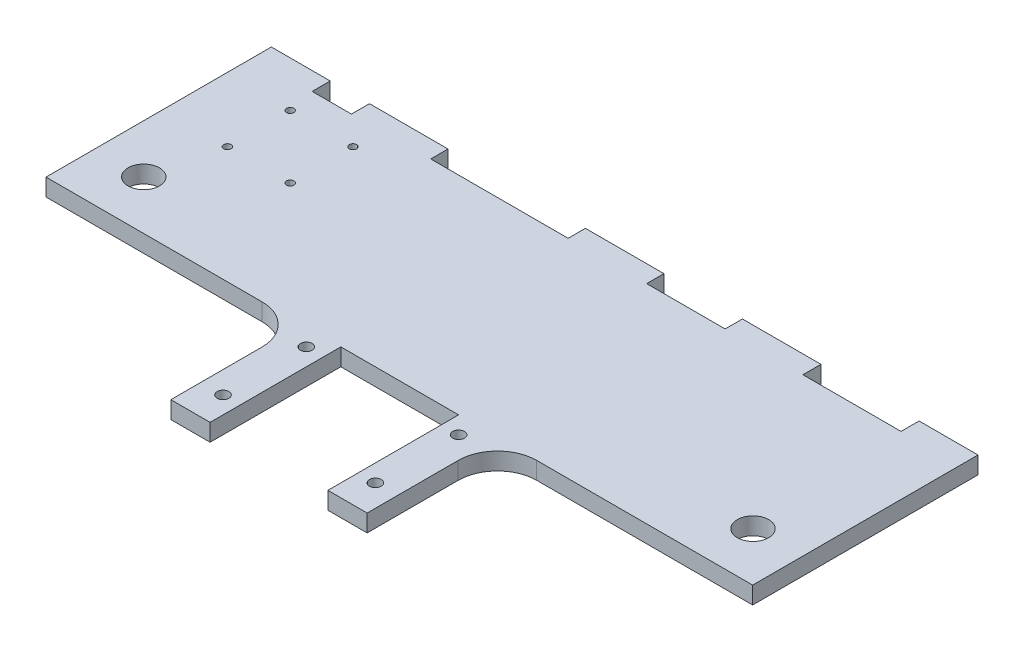
SolidWorks part; units mm, degrees
ref_plane "Front Plane" through (0, 0, 0) normal (0, 0, 1) x (1, 0, 0)
ref_plane "Top Plane" through (0, 0, 0) normal (0, 1, 0) x (1, 0, 0)
ref_plane "Right Plane" through (0, 0, 0) normal (1, 0, 0) x (0, 0, -1)
sketch "Sketch1" plane through (0, 0, 0) normal (0, 1, 0) x (1, 0, 0)
  line L0 (12.7, 67.056) -> (241.3, 67.056) construction
  line L3 (12.7, 72.898) -> (31.75, 72.898)
  line L5 (31.75, 72.898) -> (31.75, 67.056)
  line L6 (31.75, 67.056) -> (44.45, 67.056)
  line L7 (12.7, 0) -> (241.3, 0) construction
  line L8 (44.45, 67.056) -> (44.45, 72.898)
  line L10 (95.25, -42.164) -> (107.95, -42.164)
  line L12 (127, 0.1228) -> (146.05, 0.1228)
  line L13 (146.05, 0.1228) -> (146.05, -42.164)
  line L14 (127, 0.1228) -> (107.95, 0.1228)
  line L15 (107.95, 0.1228) -> (107.95, -42.164)
  line L16 (146.05, -42.164) -> (158.75, -42.164)
  line L17 (12.7, 0) -> (82.55, 0)
  line L18 (95.25, -12.7) -> (95.25, -42.164)
  line L19 (241.3, 0) -> (171.45, 0)
  line L20 (158.75, -12.7) -> (158.75, -42.164)
  line L27 (114.3, 72.898) -> (139.7, 72.898)
  line L28 (165.1, 72.898) -> (190.5, 72.898)
  line L29 (69.85, 72.898) -> (69.85, 67.31)
  line L30 (69.85, 67.31) -> (114.3, 67.31)
  line L31 (114.3, 67.31) -> (114.3, 72.898)
  line L32 (139.7, 72.898) -> (139.7, 67.31)
  line L33 (139.7, 67.31) -> (165.1, 67.31)
  line L34 (165.1, 67.31) -> (165.1, 72.898)
  line L35 (190.5, 72.898) -> (190.5, 67.056)
  line L36 (190.5, 67.056) -> (222.25, 67.056)
  line L37 (222.25, 67.056) -> (222.25, 72.898)
  line L38 (44.45, 72.898) -> (69.85, 72.898)
  line L39 (222.25, 72.898) -> (241.3, 72.898)
  line L40 (241.3, 72.898) -> (241.3, 0)
  line L41 (12.7, 72.898) -> (12.7, 0)
  arc A0 (171.45, 0) -> (158.75, -12.7) centre (171.45, -12.7) ccw
  arc A1 (95.25, -12.7) -> (82.55, 0) centre (82.55, -12.7) ccw
  point P0 (0, 0)
  point P10 (0, -41.181)
  point P27 (95.25, 0)
  dimension "D6" = 12.7
  dimension "D3" = 5.842
  dimension "D4" = 67.056
  dimension "D5" = 19.05
  dimension "D7" = 12.7
  dimension "D10" = 25.4
  dimension "D11" = 5.588
  dimension "D13" = 29.464
  dimension "D14" = 42.2868
  dimension "D15" = 12.7
  dimension "D17" = 25.4
  dimension "D20" = 228.6
extrude "Boss-Extrude1" add sketch "Sketch1" along normal blind 5.588
sketch "Sketch2" plane through (0, 0, 0) normal (0, -1, 0) x (1, 0, 0)
  point P0 (102.362, 32.3976)
  point P1 (151.638, 32.3976)
  point P3 (102.362, 5.4568)
  point P5 (151.638, 5.4568)
hole_wizard "#6 Clearance Hole1" positions "Sketch3" profile "Sketch4" hole size "#6" standard "ANSI Inch" end condition through all
sketch "Sketch3" plane through (0, 0, 0) normal (0, -1, 0) x (-1, 0, 0)
  point P0 (-102.362, -32.3976)
  point P3 (-151.638, -32.3976)
  point P6 (-151.638, -5.4568)
  point P9 (-102.362, -5.4568)
sketch "Sketch4" plane through (102.362, 0, 32.3976) normal (1, 0, 0) x (0, 0, -1)
  line L0 (0, 0) -> (0, 5.588)
  line L1 (0, 5.588) -> (1.8986, 5.588)
  line L2 (1.8986, 5.588) -> (1.8986, 0)
  line L5 (1.8986, 0) -> (0, 0)
  line L11 (0, -6.35) -> (0, 107.95) construction
  dimension "Thru Hole Dia." = 3.7973
  dimension "Thru Hole Depth" = 5.588
sketch "Sketch5" plane through (0, 5.588, 0) normal (0, 1, 0) x (1, 0, 0)
  point P0 (33.528, 58.166)
  point P1 (53.848, 58.166)
  point P3 (53.848, 37.846)
  point P5 (33.528, 37.846)
hole_wizard "M2 Clearance Hole1" positions "Sketch6" profile "Sketch7" hole size "M2" standard "ANSI Metric" end condition through all
sketch "Sketch6" plane through (0, 5.588, 0) normal (0, 1, 0) x (1, 0, 0)
  point P0 (33.528, 58.166)
  point P3 (53.848, 58.166)
  point P6 (53.848, 37.846)
  point P9 (33.528, 37.846)
sketch "Sketch7" plane through (33.528, 5.588, -58.166) normal (1, 0, 0) x (0, 0, 1)
  line L0 (0, 0) -> (0, 5.588)
  line L1 (0, 5.588) -> (1.2, 5.588)
  line L2 (1.2, 5.588) -> (1.2, 0)
  line L5 (1.2, 0) -> (0, 0)
  line L11 (0, -6.35) -> (0, 107.95) construction
  dimension "Thru Hole Dia." = 2.4
  dimension "Thru Hole Depth" = 5.588
sketch "Sketch8" plane through (0, 5.588, 0) normal (0, 1, 0) x (1, 0, 0)
  line L0 (12.7, 5.7108) -> (241.3, 5.7108) construction
  line L1 (18.288, 5.7108) -> (18.288, 73.0208) construction
  line L2 (235.712, 5.7108) -> (235.712, 73.0208) construction
  circle A0 centre (28.448, 15.8708) radius 5.08
  circle A1 centre (225.552, 15.8708) radius 5.08
  dimension "D1" = 10.16
  dimension "D3" = 10.16
  dimension "D2" = 10.16
  dimension "D4" = 10.16
  dimension "D5" = 10.16
extrude "Cut-Extrude1" cut sketch "Sketch8" against normal up to next
